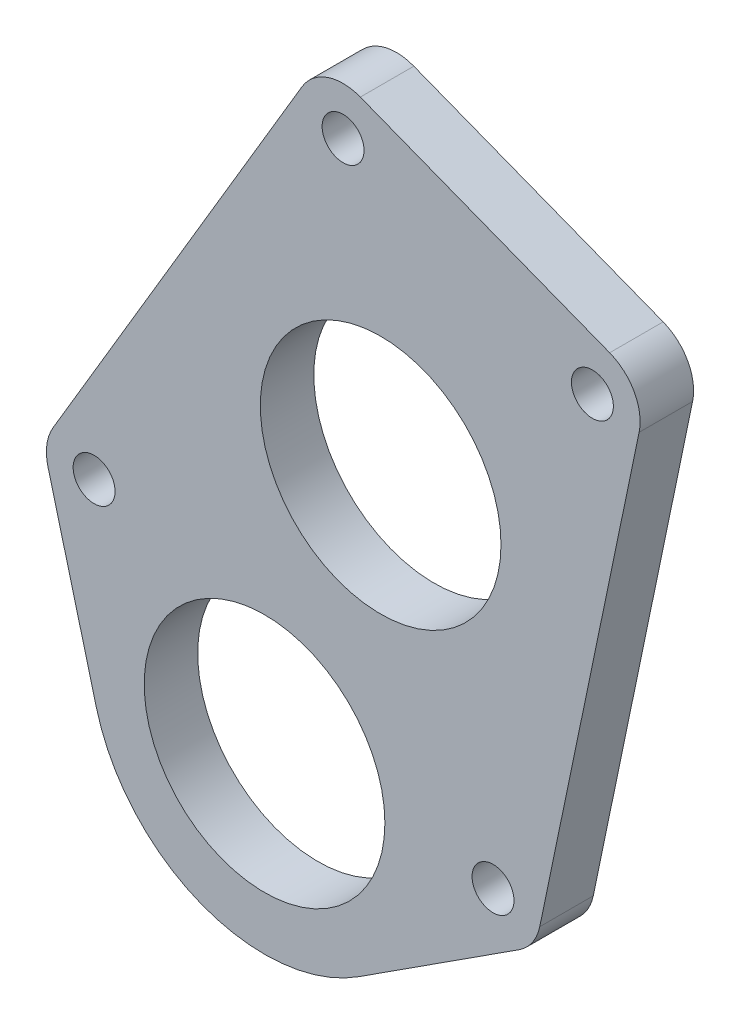
SolidWorks part; units mm, degrees
material "6061-T6 (SS)"
ref_plane "Front Plane" through (0, 0, 0) normal (0, 0, 1) x (1, 0, 0)
ref_plane "Top Plane" through (0, 0, 0) normal (0, 1, 0) x (1, 0, 0)
ref_plane "Right Plane" through (0, 0, 0) normal (1, 0, 0) x (0, 0, -1)
sketch "Sketch1" plane through (0, 0, 0) normal (0, 0, 1) x (1, 0, 0)
  line L0 (13.7841, 35.5191) -> (0, 0) construction
  line L1 (-20.2334, 18.0692) -> (27.1254, -0.3096) construction
  line L2 (13.7841, 35.5191) -> (24.1222, 62.1585) construction
  line L3 (0, 0) -> (23.1556, 0) construction
  line L4 (-25.7114, 16.6288) -> (-19.9591, -5.2481)
  line L5 (11.194, -17.3378) -> (30.1978, -5.0682)
  line L8 (9.3225, 67.9019) -> (38.9218, 56.4151) construction
  line L9 (-25.1052, 20.9586) -> (4.4508, 70.7913)
  line L10 (32.671, -1.4629) -> (44.4674, 55.2619)
  line L11 (11.3718, 73.1824) -> (40.971, 61.6956)
  circle A0 centre (0, 0) radius 14.2875
  circle A1 centre (13.7841, 35.5191) radius 14.2875
  circle A2 centre (-20.2334, 18.0692) radius 2.4892
  circle A3 centre (27.1254, -0.3096) radius 2.4892
  arc A5 (-19.9591, -5.2481) -> (11.194, -17.3378) centre (0, 0) ccw
  circle A9 centre (0, 0) radius 20.6375 construction
  circle A10 centre (38.9218, 56.4151) radius 2.4892
  circle A11 centre (9.3225, 67.9019) radius 2.4892
  arc A12 (-25.1052, 20.9586) -> (-25.7114, 16.6288) centre (-20.2334, 18.0692) ccw
  arc A13 (30.1978, -5.0682) -> (32.671, -1.4629) centre (27.1254, -0.3096) ccw
  arc A14 (44.4674, 55.2619) -> (40.971, 61.6956) centre (38.9218, 56.4151) ccw
  arc A15 (11.3718, 73.1824) -> (4.4508, 70.7913) centre (9.3225, 67.9019) ccw
  circle A16 centre (-20.2334, 18.0692) radius 5.6642 construction
  circle A17 centre (27.1254, -0.3096) radius 5.6642 construction
  circle A18 centre (38.9218, 56.4151) radius 5.6642 construction
  circle A19 centre (9.3225, 67.9019) radius 5.6642 construction
  point P17 (24.1222, 62.1585)
  point P32 (3.446, 8.8798)
  dimension "D1" = 28.575
  dimension "D3" = 4.9784
  dimension "D2" = 38.1
  dimension "D4" = 28.575
  dimension "D5" = 50.8
  dimension "D6" = 68.79
  dimension "D8" = 31.75
  dimension "D10" = 9.525
  dimension "D7" = 6.35
  dimension "D9" = 3.175
extrude "Boss-Extrude1" add sketch "Sketch1" along normal mid plane 6.35
equation "\"D2@Sketch1\"=60/40"
